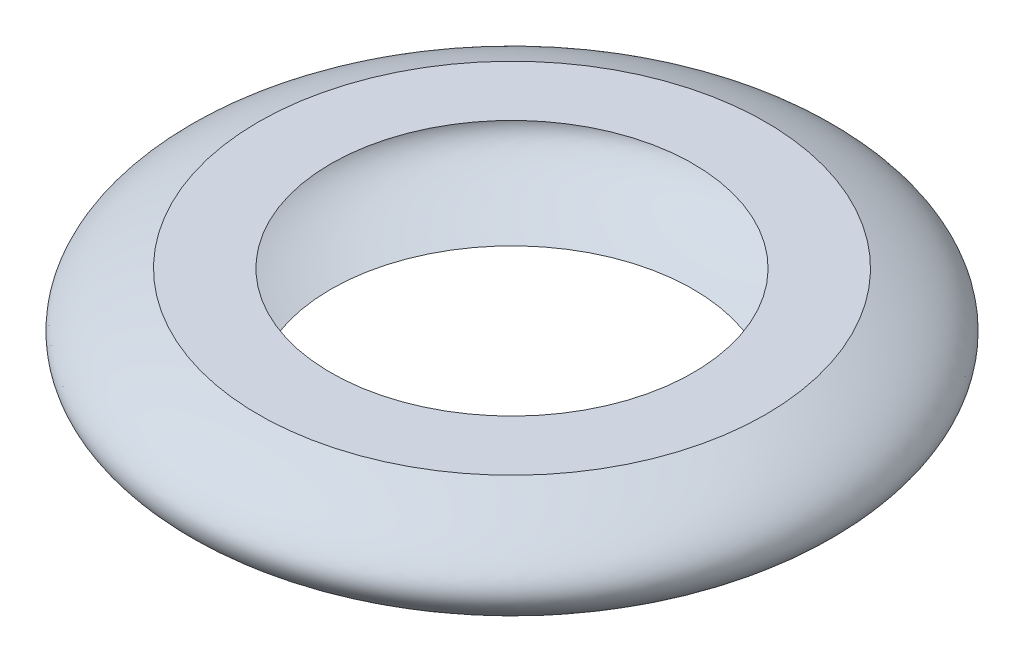
SolidWorks part; units mm, degrees
ref_plane "Front" through (0, 0, 0) normal (0, 0, 1) x (1, 0, 0)
ref_plane "Top" through (0, 0, 0) normal (0, 1, 0) x (1, 0, 0)
ref_plane "Right" through (0, 0, 0) normal (1, 0, 0) x (0, 0, -1)
sketch "Sketch1" plane through (0, 0, 0) normal (0, 1, 0) x (1, 0, 0)
  circle A0 centre (0, 0) radius 31.665
  dimension "D1" = 63.33
sketch "Sketch2" plane through (0, 0, 0) normal (0, 0, 1) x (1, 0, 0)
  line L0 (0, 0) -> (-12.5, 0) construction
  line L1 (31.665, 0) -> (-31.665, 0) construction
  line L2 (0, 3.75) -> (-23, 3.75) construction
  line L3 (0, 7.5) -> (-12.5, 7.5) construction
  line L4 (0, 7.5) -> (0, 0) construction
  line L5 (-12.5, 0) -> (-23, 3.75) construction
  line L6 (-23, 3.75) -> (-12.5, 7.5) construction
  line L7 (-17.5, 0) -> (-28, 3.75) construction
  line L8 (-28, 3.75) -> (-17.5, 7.5) construction
  line L9 (-12.5, 7.5) -> (-17.5, 7.5)
  line L10 (-12.5, 0) -> (-17.5, 0)
  spline S0 degree 2 poles (-12.5, 0) (-23, 3.75) (-12.5, 7.5) knots 0 0 0 1 1 1
  spline S1 degree 2 poles (-17.5, 0) (-28, 3.75) (-17.5, 7.5) knots 0 0 0 1 1 1
  dimension "D1" = 12.5
  dimension "D2" = 7.5
  dimension "D3" = 10.5
  dimension "D5" = 5
  dimension "D4" = 2
revolve "Revolve1" add sketch "Sketch2" angle 360 about L4
